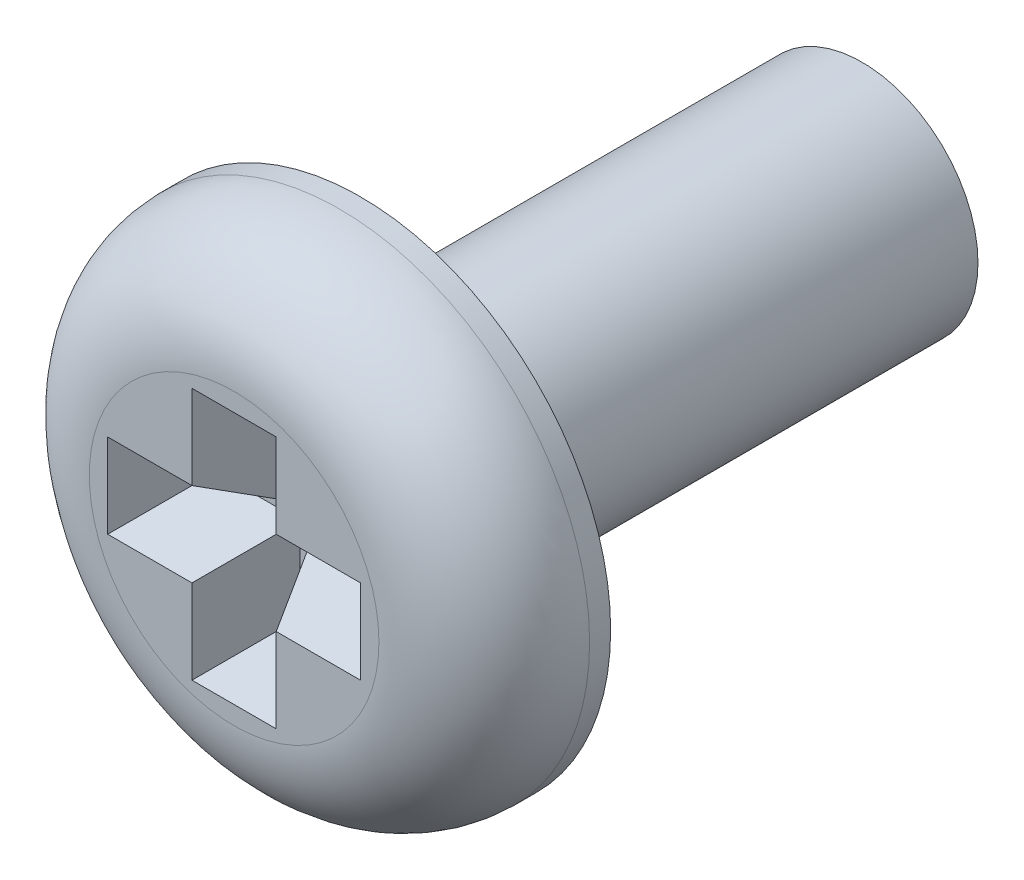
SolidWorks part; units mm, degrees
ref_plane "Front Plane" through (0, 0, 0) normal (0, 0, 1) x (1, 0, 0)
ref_plane "Top Plane" through (0, 0, 0) normal (0, 1, 0) x (1, 0, 0)
ref_plane "Right Plane" through (0, 0, 0) normal (1, 0, 0) x (0, 0, -1)
sketch "Sketch1" plane through (0, 0, 0) normal (0, 0, 1) x (1, 0, 0)
  circle A0 centre (0, 0) radius 2.375
  dimension "D1" = 4.75
extrude "Extrude1" add sketch "Sketch1" along normal blind 1.2
fillet "Fillet1" radius 1 1 edges at (2.375, 0, 1.2)
sketch "Sketch2" plane through (0, 0, 1.2) normal (0, 0, 1) x (1, 0, 0)
  line L0 (-0.4, 0.4) -> (-1.2, 0.4)
  line L1 (1.2, 0.4) -> (0.4, 0.4)
  line L2 (1.2, 0.4) -> (1.2, -0.4)
  line L3 (1.2, -0.4) -> (0.4, -0.4)
  line L4 (-1.2, 0.4) -> (-1.2, -0.4)
  line L5 (-0.4, 1.2) -> (0.4, 1.2)
  line L6 (-0.4, 1.2) -> (-0.4, 0.4)
  line L7 (-0.4, -1.2) -> (0.4, -1.2)
  line L8 (0.4, 1.2) -> (0.4, 0.4)
  line L9 (0.4, -0.4) -> (0.4, -1.2)
  line L10 (-0.4, -0.4) -> (-1.2, -0.4)
  line L11 (-0.4, -0.4) -> (-0.4, -1.2)
  dimension "D1" = 0.4
  dimension "D2" = 0.4
  dimension "D3" = 1.2
  dimension "D4" = 1.2
  dimension "D5" = 0.4
  dimension "D6" = 0.4
  dimension "D7" = 1.2
  dimension "D8" = 1.2
extrude "Cut-Extrude1" cut sketch "Sketch2" against normal blind 0.7 draft 25
sketch "Sketch3" plane through (0, 0, 0) normal (0, 0, -1) x (-1, 0, 0)
  circle A0 centre (0, 0) radius 1.1
  dimension "D1" = 2.2
extrude "Extrude2" add sketch "Sketch3" along normal blind 4.7625
